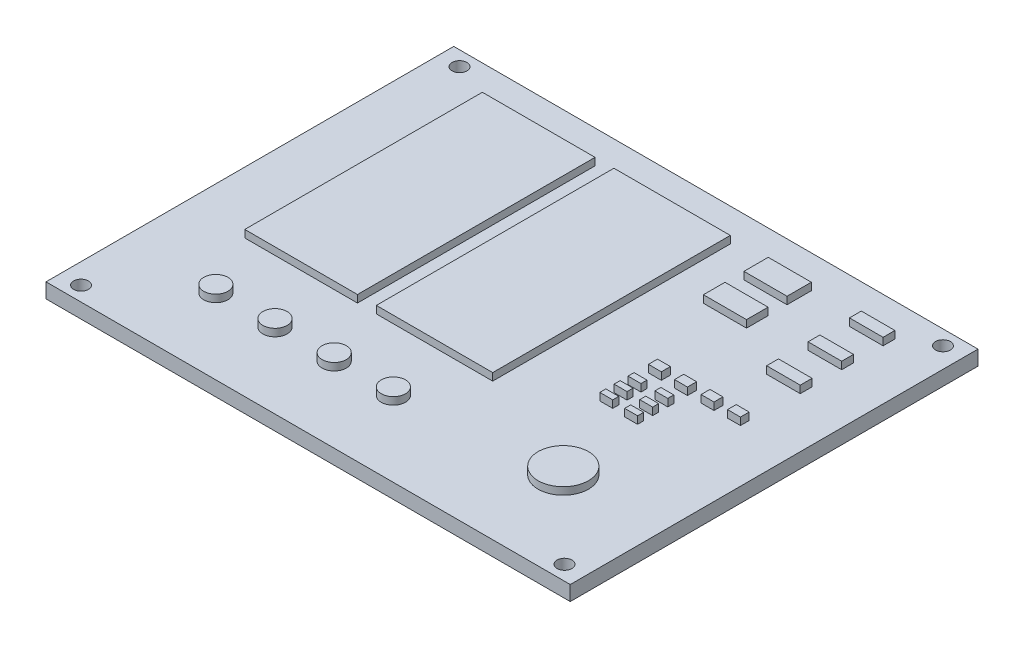
SolidWorks part; units mm, degrees
ref_plane "Front Plane" through (0, 0, 0) normal (0, 0, 1) x (1, 0, 0)
ref_plane "Top Plane" through (0, 0, 0) normal (0, 1, 0) x (1, 0, 0)
ref_plane "Right Plane" through (0, 0, 0) normal (1, 0, 0) x (0, 0, -1)
sketch "Sketch1" plane through (0, 0, 0) normal (0, 1, 0) x (1, 0, 0)
  line L0 (45, -35) -> (45, 35)
  line L1 (45, -35) -> (-45, -35)
  line L2 (45, 35) -> (-45, 35)
  line L3 (-45, -35) -> (-45, 35)
  line L4 (45, -35) -> (-45, 35) construction
  line L5 (45, 35) -> (-45, -35) construction
  line L6 (27.8186, 3.2776) -> (30.0383, 3.2776)
  line L7 (-35.8955, 27.9187) -> (-16.5455, 27.9187)
  line L8 (-35.8955, 27.9187) -> (-35.8955, -12.8687)
  line L9 (-35.8955, -12.8687) -> (-16.5455, -12.8687)
  line L10 (-16.5455, 27.9187) -> (-16.5455, -12.8687)
  line L11 (-13.3076, 27.9187) -> (6.6703, 27.9187)
  line L12 (-13.3076, 27.9187) -> (-13.3076, -12.8687)
  line L13 (-13.3076, -12.8687) -> (6.6703, -12.8687)
  line L14 (6.6703, 27.9187) -> (6.6703, -12.8687)
  line L15 (13.1816, 27.9187) -> (20.5808, 27.9187)
  line L16 (13.1816, 27.9187) -> (13.1816, 23.7484)
  line L17 (13.1816, 23.7484) -> (20.5808, 23.7484)
  line L18 (20.5808, 27.9187) -> (20.5808, 23.7484)
  line L19 (13.1816, 20.4928) -> (20.5808, 20.4928)
  line L20 (13.1816, 20.4928) -> (13.1816, 16.7931)
  line L21 (13.1816, 16.7931) -> (20.5808, 16.7931)
  line L22 (20.5808, 20.4928) -> (20.5808, 16.7931)
  line L23 (29.1639, 27.9187) -> (34.9353, 27.9187)
  line L24 (29.1639, 27.9187) -> (29.1639, 25.8867)
  line L25 (29.1639, 25.8867) -> (34.9353, 25.8867)
  line L26 (34.9353, 27.9187) -> (34.9353, 25.8867)
  line L27 (29.1639, 20.8067) -> (34.9353, 20.8067)
  line L28 (29.1639, 20.8067) -> (29.1639, 18.7747)
  line L29 (29.1639, 18.7747) -> (34.9353, 18.7747)
  line L30 (34.9353, 20.8067) -> (34.9353, 18.7747)
  line L31 (29.1639, 13.6947) -> (34.9353, 13.6947)
  line L32 (29.1639, 13.6947) -> (29.1639, 11.6627)
  line L33 (29.1639, 11.6627) -> (34.9353, 11.6627)
  line L34 (34.9353, 13.6947) -> (34.9353, 11.6627)
  line L35 (18.8071, -0.7396) -> (21.0268, -0.7396)
  line L36 (18.8071, -0.7396) -> (18.8071, -1.7755)
  line L37 (18.8071, -1.7755) -> (21.0268, -1.7755)
  line L38 (21.0268, -0.7396) -> (21.0268, -1.7755)
  line L39 (23.3128, 3.2776) -> (25.5326, 3.2776)
  line L40 (23.3128, 3.2776) -> (23.3128, 1.6988)
  line L41 (23.3128, 1.6988) -> (25.5326, 1.6988)
  line L42 (25.5326, 3.2776) -> (25.5326, 1.6988)
  line L59 (27.8186, 3.2776) -> (27.8186, 1.7531)
  line L60 (27.8186, 1.7531) -> (30.0383, 1.7531)
  line L61 (30.0383, 3.2776) -> (30.0383, 1.7531)
  line L62 (18.8071, 3.2776) -> (21.0268, 3.2776)
  line L63 (18.8071, 3.2776) -> (18.8071, 1.7238)
  line L64 (18.8071, 1.7238) -> (21.0268, 1.7238)
  line L65 (21.0268, 3.2776) -> (21.0268, 1.7238)
  line L66 (32.3243, 3.2776) -> (34.5441, 3.2776)
  line L67 (32.3243, 3.2776) -> (32.3243, 1.7838)
  line L68 (32.3243, 1.7838) -> (34.5441, 1.7838)
  line L69 (34.5441, 3.2776) -> (34.5441, 1.7838)
  line L70 (18.8071, -3.1284) -> (21.0268, -3.1284)
  line L71 (18.8071, -3.1284) -> (18.8071, -4.1642)
  line L72 (18.8071, -4.1642) -> (21.0268, -4.1642)
  line L73 (21.0268, -3.1284) -> (21.0268, -4.1642)
  line L74 (18.8071, -5.5844) -> (21.0268, -5.5844)
  line L75 (18.8071, -5.5844) -> (18.8071, -6.6203)
  line L76 (18.8071, -6.6203) -> (21.0268, -6.6203)
  line L77 (21.0268, -5.5844) -> (21.0268, -6.6203)
  line L78 (23.3128, -0.6431) -> (25.5326, -0.6431)
  line L79 (23.3128, -0.6431) -> (23.3128, -1.679)
  line L80 (23.3128, -1.679) -> (25.5326, -1.679)
  line L81 (25.5326, -0.6431) -> (25.5326, -1.679)
  line L82 (23.3128, -3.2331) -> (25.5326, -3.2331)
  line L83 (23.3128, -3.2331) -> (23.3128, -4.269)
  line L84 (23.3128, -4.269) -> (25.5326, -4.269)
  line L85 (25.5326, -3.2331) -> (25.5326, -4.269)
  line L86 (23.3128, -5.8231) -> (25.5326, -5.8231)
  line L87 (23.3128, -5.8231) -> (23.3128, -6.859)
  line L88 (23.3128, -6.859) -> (25.5326, -6.859)
  line L89 (25.5326, -5.8231) -> (25.5326, -6.859)
  circle A0 centre (-30.2235, -23.5072) radius 2.0748
  circle A1 centre (-20.0635, -23.5072) radius 2.0748
  circle A2 centre (-9.9035, -23.5072) radius 2.0748
  circle A3 centre (0.2565, -23.5072) radius 2.0748
  circle A4 centre (26.6406, -20.7205) radius 4.3252
  point P1 (0, 0)
  dimension "D1" = 90
  dimension "D2" = 70
  dimension "D3" = 5.08
  dimension "D4" = 5.08
  dimension "D5" = 2.032
  dimension "D6" = 2.032
  dimension "D7" = 2.032
  dimension "D8" = 2.286
  dimension "D9" = 2.286
  dimension "D10" = 2.286
  dimension "D11" = 10.16
  dimension "D12" = 10.16
  dimension "D13" = 10.16
extrude "Boss-Extrude1" add sketch "Sketch1" along normal blind 2.54 contours L10 L7 L8 L9 | L14 L11 L12 L13 | L18 L15 L16 L17 | L22 L19 L20 L21 | L69 L66 L67 L68 | L61 L6 L59 L60 | L42 L39 L40 L41 | L65 L62 L63 L64 | L38 L35 L36 L37 | L85 L82 L83 L84 | L81 L78 L79 L80 | A4 | A3 | A2 | A1 | A0 | L3 L1 L0 L2 A4 A3 A2 A1 A0 L7 L10 L9 L8 L11 L14 L13 L12 L15 L18 L17 L16 L19 L22 L21 L20 L23 L26 L25 L24 L27 L30 L29 L28 L31 L34 L33 L32 L35 | L70 L73 L72 L71 | L74 L77 L76 L75 | L86 L89 L88 L87
sketch "Sketch2" plane through (0, 2.54, 0) normal (0, 1, 0) x (1, 0, 0)
  line L0 (29.2545, 4.7284) -> (31.4742, 4.7284)
  line L1 (-34.4596, 29.3695) -> (-15.1096, 29.3695)
  line L2 (-34.4596, 29.3695) -> (-34.4596, -11.4179)
  line L3 (-34.4596, -11.4179) -> (-15.1096, -11.4179)
  line L4 (-15.1096, 29.3695) -> (-15.1096, -11.4179)
  line L5 (-11.8717, 29.3695) -> (8.1062, 29.3695)
  line L6 (-11.8717, 29.3695) -> (-11.8717, -11.4179)
  line L7 (-11.8717, -11.4179) -> (8.1062, -11.4179)
  line L8 (8.1062, 29.3695) -> (8.1062, -11.4179)
  line L9 (14.6175, 29.3695) -> (22.0167, 29.3695)
  line L10 (14.6175, 29.3695) -> (14.6175, 25.1992)
  line L11 (14.6175, 25.1992) -> (22.0167, 25.1992)
  line L12 (22.0167, 29.3695) -> (22.0167, 25.1992)
  line L13 (14.6175, 21.9436) -> (22.0167, 21.9436)
  line L14 (14.6175, 21.9436) -> (14.6175, 18.244)
  line L15 (14.6175, 18.244) -> (22.0167, 18.244)
  line L16 (22.0167, 21.9436) -> (22.0167, 18.244)
  line L17 (30.5998, 29.3695) -> (36.3712, 29.3695)
  line L18 (30.5998, 29.3695) -> (30.5998, 27.3375)
  line L19 (30.5998, 27.3375) -> (36.3712, 27.3375)
  line L20 (36.3712, 29.3695) -> (36.3712, 27.3375)
  line L21 (30.5998, 22.2575) -> (36.3712, 22.2575)
  line L22 (30.5998, 22.2575) -> (30.5998, 20.2255)
  line L23 (30.5998, 20.2255) -> (36.3712, 20.2255)
  line L24 (36.3712, 22.2575) -> (36.3712, 20.2255)
  line L25 (30.5998, 15.1455) -> (36.3712, 15.1455)
  line L26 (30.5998, 15.1455) -> (30.5998, 13.1135)
  line L27 (30.5998, 13.1135) -> (36.3712, 13.1135)
  line L28 (36.3712, 15.1455) -> (36.3712, 13.1135)
  line L29 (20.243, 0.7112) -> (22.4627, 0.7112)
  line L30 (20.243, 0.7112) -> (20.243, -0.3247)
  line L31 (20.243, -0.3247) -> (22.4627, -0.3247)
  line L32 (22.4627, 0.7112) -> (22.4627, -0.3247)
  line L33 (24.7487, 4.7284) -> (26.9685, 4.7284)
  line L34 (24.7487, 4.7284) -> (24.7487, 3.1496)
  line L35 (24.7487, 3.1496) -> (26.9685, 3.1496)
  line L36 (26.9685, 4.7284) -> (26.9685, 3.1496)
  line L37 (29.2545, 4.7284) -> (29.2545, 3.2039)
  line L38 (29.2545, 3.2039) -> (31.4742, 3.2039)
  line L39 (31.4742, 4.7284) -> (31.4742, 3.2039)
  line L40 (20.243, 4.7284) -> (22.4627, 4.7284)
  line L41 (20.243, 4.7284) -> (20.243, 3.1746)
  line L42 (20.243, 3.1746) -> (22.4627, 3.1746)
  line L43 (22.4627, 4.7284) -> (22.4627, 3.1746)
  line L44 (33.7602, 4.7284) -> (35.98, 4.7284)
  line L45 (33.7602, 4.7284) -> (33.7602, 3.2346)
  line L46 (33.7602, 3.2346) -> (35.98, 3.2346)
  line L47 (35.98, 4.7284) -> (35.98, 3.2346)
  line L48 (20.243, -1.6775) -> (22.4627, -1.6775)
  line L49 (20.243, -1.6775) -> (20.243, -2.7134)
  line L50 (20.243, -2.7134) -> (22.4627, -2.7134)
  line L51 (22.4627, -1.6775) -> (22.4627, -2.7134)
  line L52 (20.243, -4.1336) -> (22.4627, -4.1336)
  line L53 (20.243, -4.1336) -> (20.243, -5.1695)
  line L54 (20.243, -5.1695) -> (22.4627, -5.1695)
  line L55 (22.4627, -4.1336) -> (22.4627, -5.1695)
  line L56 (24.7487, 0.8077) -> (26.9685, 0.8077)
  line L57 (24.7487, 0.8077) -> (24.7487, -0.2282)
  line L58 (24.7487, -0.2282) -> (26.9685, -0.2282)
  line L59 (26.9685, 0.8077) -> (26.9685, -0.2282)
  line L60 (24.7487, -1.7823) -> (26.9685, -1.7823)
  line L61 (24.7487, -1.7823) -> (24.7487, -2.8182)
  line L62 (24.7487, -2.8182) -> (26.9685, -2.8182)
  line L63 (26.9685, -1.7823) -> (26.9685, -2.8182)
  line L64 (24.7487, -4.3723) -> (26.9685, -4.3723)
  line L65 (24.7487, -4.3723) -> (24.7487, -5.4081)
  line L66 (24.7487, -5.4081) -> (26.9685, -5.4081)
  line L67 (26.9685, -4.3723) -> (26.9685, -5.4081)
  circle A0 centre (-28.7876, -22.0564) radius 2.0748
  circle A1 centre (-18.6276, -22.0564) radius 2.0748
  circle A2 centre (-8.4676, -22.0564) radius 2.0748
  circle A3 centre (1.6924, -22.0564) radius 2.0748
  circle A4 centre (28.0765, -19.2697) radius 4.3252
extrude "Boss-Extrude2" add sketch "Sketch2" along normal blind 1.27
sketch "Sketch3" plane through (0, 2.54, 0) normal (0, 1, 0) x (1, 0, 0)
  line L0 (-45, -35) -> (-45, 35) construction
  line L1 (45, 35) -> (-45, 35) construction
  circle A0 centre (-41.4986, 32.4854) radius 1.27
  dimension "D3" = 2.54
  dimension "D1" = 3.5014
  dimension "D2" = 2.5146
extrude "Cut-Extrude1" cut sketch "Sketch3" against normal blind 2.54
ref_plane "Plane1" through (0, 0, 0) normal (-1, 0, 0) x (0, 0, 1)
ref_plane "Plane2" through (0, 0, 0) normal (0, 0, -1) x (-1, 0, 0)
mirror "Mirror1" about plane through (0, 0, 0) normal (0, 0, -1) of "Cut-Extrude1"
mirror "Mirror2" about plane through (0, 0, 0) normal (-1, 0, 0) of "Mirror1", "Cut-Extrude1"
